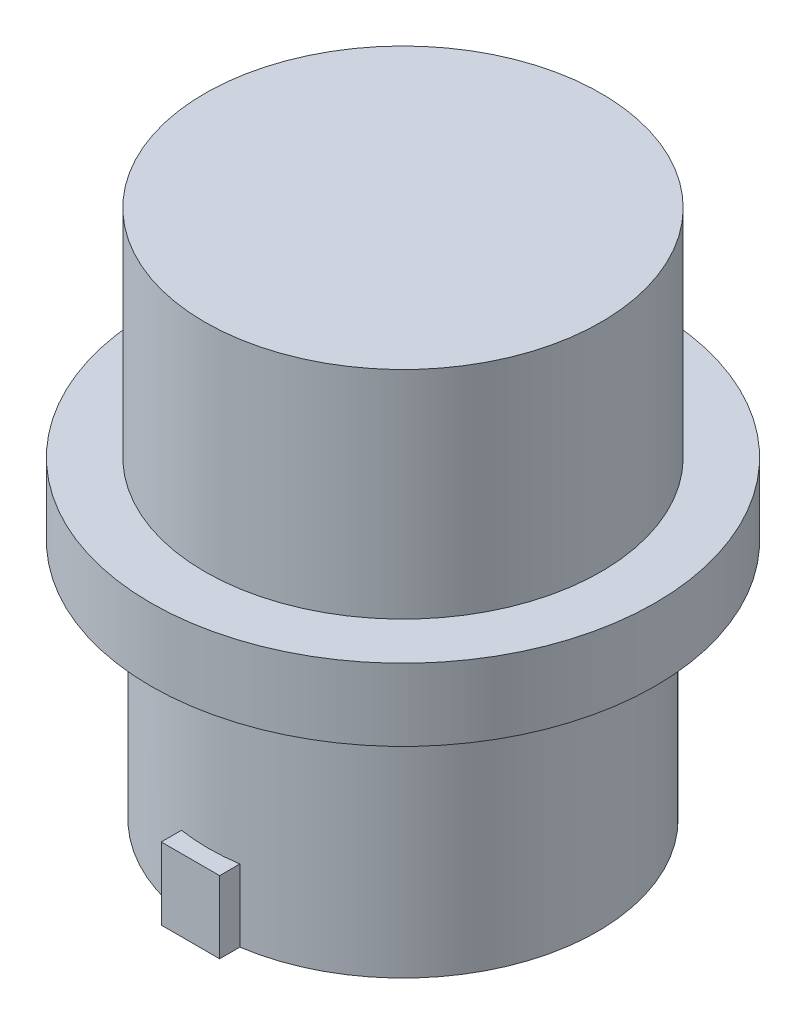
SolidWorks part; units mm, degrees
ref_plane "Ebene vorne" through (0, 0, 0) normal (0, 0, 1) x (1, 0, 0)
ref_plane "Ebene oben" through (0, 0, 0) normal (0, 1, 0) x (1, 0, 0)
ref_plane "Ebene rechts" through (0, 0, 0) normal (1, 0, 0) x (0, 0, -1)
sketch "Skizze2" plane through (0, 0, 0) normal (0, 1, 0) x (1, 0, 0)
  circle A0 centre (0, 0) radius 7
extrude "Aufsatz-Linear austragen2" add sketch "Skizze2" along normal blind 2 contours A0
sketch "Skizze4" plane through (0, 2, 0) normal (0, 1, 0) x (1, 0, 0)
  circle A0 centre (0, 0) radius 5.5
extrude "Aufsatz-Linear austragen3" add sketch "Skizze4" along normal blind 6
sketch "Skizze5" plane through (0, 0, 0) normal (0, -1, 0) x (-1, 0, 0)
  circle A0 centre (0, 0) radius 5.4
  point P3 (0, 0)
extrude "Aufsatz-Linear austragen4" add sketch "Skizze5" along normal blind 6.7
sketch "Skizze7" plane through (0, -6.7, 0) normal (0, -1, 0) x (1, 0, 0)
  line L1 (-0.81, 4.9) -> (0.81, 4.9)
  line L2 (-0.81, 4.9) -> (-0.81, 5.9)
  line L3 (-0.81, 5.9) -> (0.81, 5.9)
  line L4 (0.81, 4.9) -> (0.81, 5.9)
  line L5 (-0.81, 4.9) -> (0.81, 5.9) construction
  line L6 (-0.81, 5.9) -> (0.81, 4.9) construction
  circle A0 centre (0, 0) radius 5.4 construction
  circle A1 centre (0, 0) radius 5.4 construction
  point P0 (0, 5.4)
  dimension "D1" = 0.5
extrude "Aufsatz-Linear austragen5" add sketch "Skizze7" against normal blind 2
